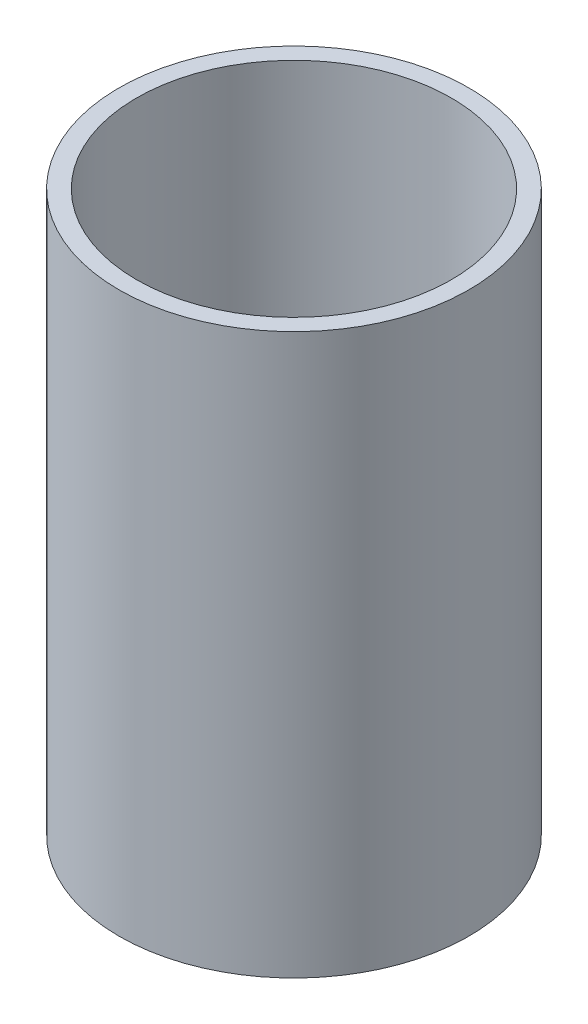
SolidWorks part; units mm, degrees
ref_plane "Front Plane" through (0, 0, 0) normal (0, 0, 1) x (1, 0, 0)
ref_plane "Top Plane" through (0, 0, 0) normal (0, 1, 0) x (1, 0, 0)
ref_plane "Right Plane" through (0, 0, 0) normal (1, 0, 0) x (0, 0, -1)
sketch "Sketch1" plane through (0, 0, 0) normal (0, 1, 0) x (1, 0, 0)
  circle A1 centre (-3.4878, 0.9926) radius 2.5
  dimension "D2" = 5
extrude "Boss-Extrude2" add sketch "Sketch1" along normal blind 8
sketch "Sketch2" plane through (0, 8, 0) normal (0, 1, 0) x (1, 0, 0)
  circle A0 centre (-3.4878, 0.9926) radius 2.25
  dimension "D1" = 4.5
extrude "Cut-Extrude1" cut sketch "Sketch2" against normal blind 7.2
